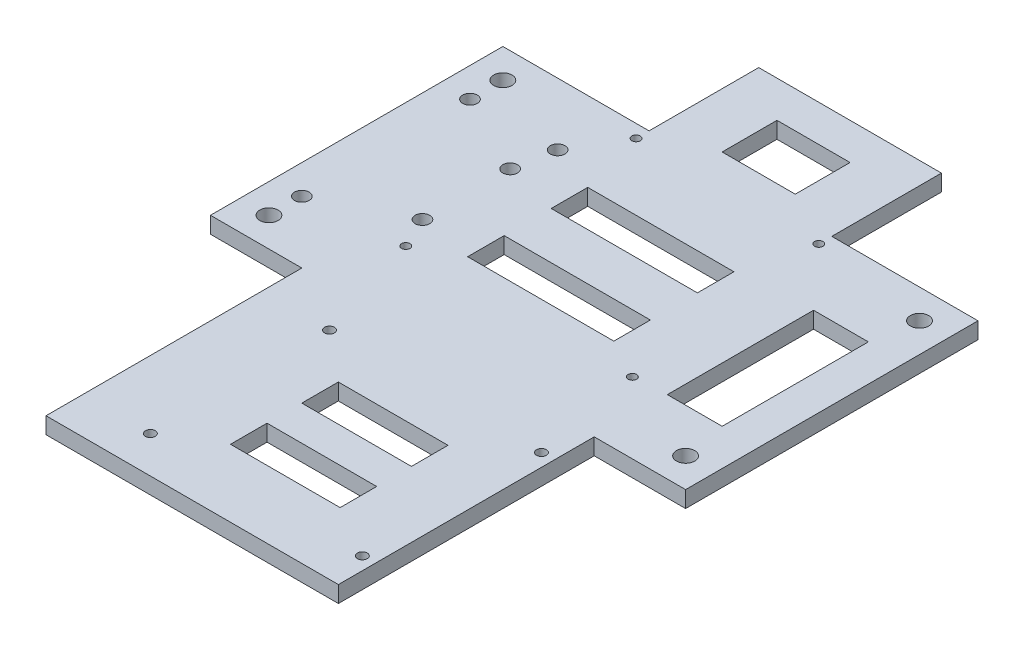
SolidWorks part; units mm, degrees
ref_plane "前视基准面" through (0, 0, 0) normal (0, 0, 1) x (1, 0, 0)
ref_plane "上视基准面" through (0, 0, 0) normal (0, 1, 0) x (1, 0, 0)
ref_plane "右视基准面" through (0, 0, 0) normal (1, 0, 0) x (0, 0, -1)
sketch "草图2" plane through (0, 0, 0) normal (0, 1, 0) x (1, 0, 0)
  line L0 (0, 15) -> (13.3734, 15) construction
  line L1 (-65, 55) -> (65, 55)
  line L2 (-65, 55) -> (-65, -25)
  line L3 (-65, -25) -> (65, -25)
  line L4 (65, 55) -> (65, -25)
  line L5 (-65, 55) -> (65, -25) construction
  line L6 (-65, -25) -> (65, 55) construction
  line L7 (0, 15) -> (0, 31.4747) construction
  circle A10 centre (-57, 47) radius 2.5
  circle A11 centre (57, 47) radius 2.5
  circle A12 centre (57, -17) radius 2.5
  circle A13 centre (-57, -17) radius 2.5
  dimension "D2" = 8
  dimension "D3" = 5
  dimension "D4" = 8
  dimension "D9" = 130
  dimension "D10" = 80
extrude "凸台-拉伸1" add sketch "草图2" along normal blind 4.5
sketch "草图4" plane through (0, 0, 0) normal (0, -1, 0) x (1, 0, 0)
  line L0 (-65, 25) -> (65, 25) construction
  line L1 (-40, 95) -> (40, 95)
  line L2 (-40, 95) -> (-40, 25)
  line L4 (40, 95) -> (40, 25)
  line L5 (-40, 25) -> (40, 25)
  point P1 (0, 25)
  point P8 (0, 0)
  dimension "D1" = 80
  dimension "D2" = 70
extrude "凸台-拉伸2" add sketch "草图4" against normal up to surface (4.5 mm away) up to face at (57, 4.5, 19.5)
sketch "草图6" plane through (0, 0, 0) normal (0, -1, 0) x (1, 0, 0)
  line L0 (0, 0) -> (0, 21.3873) construction
  arc A4 (25.0058, -50.2862) -> (24.514, -52.4784) centre (25, -51.4362) ccw construction
  arc A5 (25.0058, -50.2862) -> (24.514, -52.4784) centre (25, -51.4362) ccw
  circle A8 centre (-31, 5.5638) radius 1.15
  circle A13 centre (31, 5.5638) radius 1.15
  dimension "D1" = 2.3
  dimension "D2" = 62
extrude "切除-拉伸2" cut sketch "草图6" against normal up to surface (4.5 mm away) contours A8 | A13 up to face at (57, 4.5, 19.5)
sketch "草图7" plane through (0, 0, 0) normal (0, -1, 0) x (1, 0, 0)
  line L1 (0, 0) -> (0, -9.7574) construction
  circle A1 centre (31, 5.5638) radius 1.15 construction
  circle A3 centre (31, 5.5638) radius 1.15
  circle A4 centre (-25, -51.4362) radius 1.15
  circle A5 centre (25, -51.4362) radius 1.15
  dimension "D1" = 57
  dimension "D2" = 50
extrude "切除-拉伸3" cut sketch "草图7" against normal up to surface (4.5 mm away) up to face at (-31, 4.5, 6.7138)
sketch "草图8" plane through (0, 0, 0) normal (0, -1, 0) x (1, 0, 0)
  arc A0 (-21.5077, 37.2728) -> (-21.5077, 34.5728) centre (-21.5077, 35.9228) ccw construction
  arc A2 (-21.5048, 86.2866) -> (-21.5048, 83.5866) centre (-21.5048, 84.9366) ccw construction
  arc A4 (36.4733, 86.2708) -> (36.4733, 83.5708) centre (36.4733, 84.9208) ccw construction
  arc A6 (36.4823, 37.2838) -> (36.4823, 34.5838) centre (36.4823, 35.9338) ccw construction
  circle A8 centre (-21.5048, 84.9366) radius 1.35
  circle A9 centre (36.4733, 84.9208) radius 1.35
  circle A10 centre (36.4823, 35.9338) radius 1.35
  circle A11 centre (-21.5077, 35.9228) radius 1.35
extrude "切除-拉伸4" cut sketch "草图8" against normal blind 10
sketch "草图9" plane through (0, 0, 0) normal (0, -1, 0) x (1, 0, 0)
  line L0 (40, 25) -> (40, 95) construction
  line L1 (-20, -0.3621) -> (20, -0.3621)
  line L2 (-20, -0.3621) -> (-20, -10.3621)
  line L3 (-20, -10.3621) -> (20, -10.3621)
  line L4 (20, -0.3621) -> (20, -10.3621)
  line L5 (-20, -23.2246) -> (20, -23.2246)
  line L6 (-20, -23.2246) -> (-20, -33.2246)
  line L7 (-20, -33.2246) -> (20, -33.2246)
  line L8 (20, -23.2246) -> (20, -33.2246)
  line L9 (-8, 76.5261) -> (22, 76.5261)
  line L10 (-8, 76.5261) -> (-8, 66.5261)
  line L11 (-8, 66.5261) -> (22, 66.5261)
  line L12 (22, 76.5261) -> (22, 66.5261)
  line L13 (-8, 57.0128) -> (22, 57.0128)
  line L14 (-8, 57.0128) -> (-8, 47.0128)
  line L15 (-8, 47.0128) -> (22, 47.0128)
  line L16 (22, 57.0128) -> (22, 47.0128)
  point P16 (0, -23.2246)
  dimension "D1" = 30
  dimension "D2" = 10
  dimension "D3" = 30
  dimension "D4" = 10
  dimension "D5" = 40
  dimension "D6" = 10
  dimension "D7" = 10
  dimension "D8" = 40
  dimension "D9" = 18
extrude "切除-拉伸5" cut sketch "草图9" against normal blind 10
sketch "草图11" plane through (0, 0, 0) normal (0, -1, 0) x (1, 0, 0)
  line L0 (65, -55) -> (-65, -55) construction
  line L1 (-25, -55) -> (25, -55)
  line L2 (-25, -55) -> (-25, -85)
  line L3 (-25, -85) -> (25, -85)
  line L4 (25, -55) -> (25, -85)
  point P6 (0, -55)
  dimension "D1" = 50
  dimension "D2" = 30
extrude "凸台-拉伸3" add sketch "草图11" against normal up to surface (4.5 mm away) up to face at (0, 4.5, -28.2246)
sketch "草图12" plane through (0, 0, 0) normal (0, -1, 0) x (1, 0, 0)
  line L1 (-10, -60) -> (10, -60)
  line L2 (-10, -60) -> (-10, -75)
  line L3 (-10, -75) -> (10, -75)
  line L4 (10, -60) -> (10, -75)
  line L5 (-25, -85) -> (25, -85) construction
  line L6 (-25, -85) -> (25, -85)
  point P6 (0, -75)
  dimension "D1" = 15
  dimension "D2" = 10
  dimension "D3" = 20
extrude "切除-拉伸6" cut sketch "草图12" against normal blind 10 contours L4 L1 L2 L3
sketch "草图13" plane through (0, 0, 0) normal (0, -1, 0) x (1, 0, 0)
  line L0 (-65, 25) -> (-40, 25) construction
  line L13 (65, -55) -> (65, 25)
  line L14 (65, 25) -> (40, 25)
  line L15 (40, 25) -> (40, 95)
  line L16 (40, 95) -> (-40, 95)
  line L17 (-40, 95) -> (-40, 25)
  line L18 (-40, 25) -> (-65, 25)
  line L19 (-65, 25) -> (-65, -55)
  line L20 (-65, -55) -> (-25, -55)
  line L21 (-25, -55) -> (-25, -85)
  line L22 (-25, -85) -> (25, -85)
  line L23 (25, -85) -> (25, -55)
  line L24 (25, -55) -> (65, -55)
  line L25 (65, -55) -> (65, 25)
  line L26 (65, 25) -> (40, 25)
  line L27 (40, 25) -> (40, 95)
  line L28 (40, 95) -> (-40, 95)
  line L29 (-40, 95) -> (-40, 25)
  line L30 (-40, 25) -> (-65, 25)
  line L31 (-65, 25) -> (-65, -55)
  line L32 (-65, -55) -> (-25, -55)
  line L33 (-25, -55) -> (-25, -85)
  line L34 (-25, -85) -> (25, -85)
  line L35 (25, -85) -> (25, -55)
  line L36 (25, -55) -> (65, -55)
  circle A0 centre (-57, 8) radius 2
  circle A1 centre (-33, 8) radius 2
  circle A2 centre (-57, -38) radius 2
  circle A3 centre (-33, -38) radius 2
  circle A5 centre (-57, 17) radius 2.5 construction
  circle A6 centre (-57, 17) radius 2.5
  circle A8 centre (-57, -47) radius 2.5 construction
  circle A9 centre (-57, -47) radius 2.5
  point P8 (0, 0)
  point P9 (0, 0)
  point P10 (0, 0)
  point P11 (0, 0)
  point P12 (0, 0)
  dimension "D1" = 4
  dimension "D2" = 46
  dimension "D3" = 24
  dimension "D5" = 0
  dimension "D6" = 8
  dimension "D4" = 17
extrude "切除-拉伸7" cut sketch "草图13" against normal blind 10 contours A3 | A0 | A2
sketch "草图14" plane through (0, 0, 0) normal (0, -1, 0) x (1, 0, 0)
  line L0 (-65, 25) -> (-40, 25) construction
  line L1 (-65, 25) -> (-40, 25)
  line L2 (-20, -23.2246) -> (-20, -33.2246) construction
  circle A0 centre (-35, -3) radius 2
  circle A1 centre (-35, -27) radius 2
  point P8 (0, 0)
  dimension "D1" = 4
  dimension "D2" = 4
  dimension "D5" = 15
  dimension "D3" = 24
  dimension "D4" = 28
extrude "切除-拉伸8" cut sketch "草图14" against normal blind 10 contours A1 | A0
sketch "草图15" plane through (0, 0, 0) normal (0, -1, 0) x (1, 0, 0)
  line L0 (40, 25) -> (65, 25) construction
  line L1 (40, 5) -> (55, 5)
  line L2 (40, 5) -> (40, -35)
  line L3 (40, -35) -> (55, -35)
  line L4 (55, 5) -> (55, -35)
  line L5 (65, 25) -> (65, -55) construction
  dimension "D1" = 15
  dimension "D2" = 40
  dimension "D3" = 20
  dimension "D4" = 10
extrude "切除-拉伸9" cut sketch "草图15" against normal blind 10
